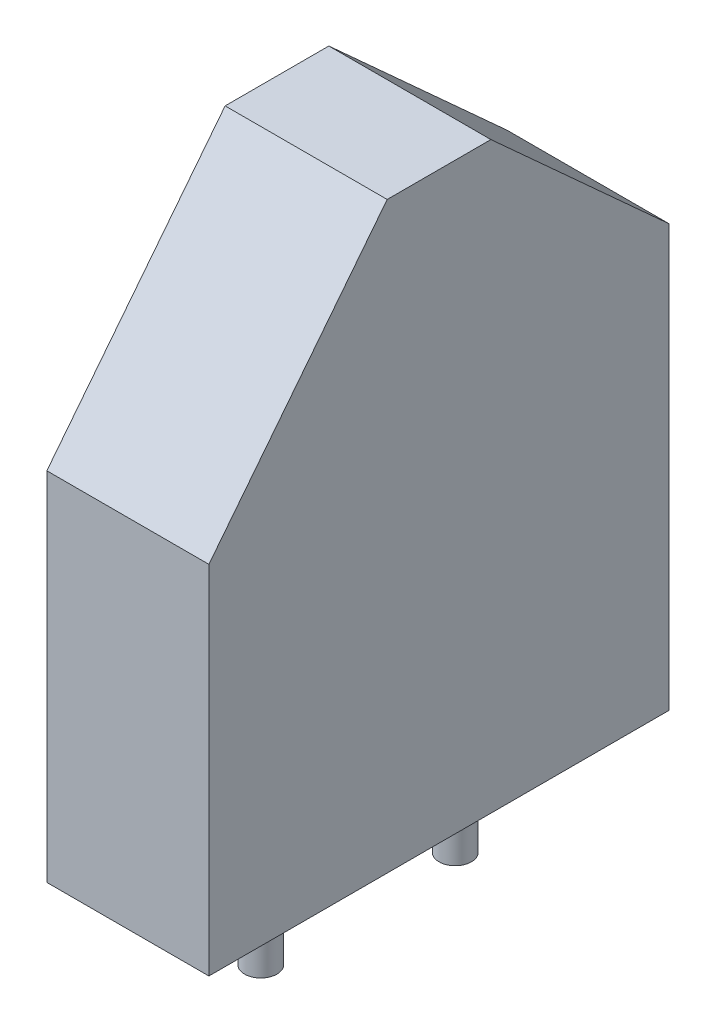
SolidWorks part; units mm, degrees
ref_plane "前视基准面" through (0, 0, 0) normal (0, 0, 1) x (1, 0, 0)
ref_plane "上视基准面" through (0, 0, 0) normal (0, 1, 0) x (1, 0, 0)
ref_plane "右视基准面" through (0, 0, 0) normal (1, 0, 0) x (0, 0, -1)
sketch "草图1" plane through (0, 0, 0) normal (0, 1, 0) x (1, 0, 0)
  line L0 (-45.7415, 0) -> (52.4503, 0) construction
  line L1 (-2.5, 7.1) -> (2.5, 7.1)
  line L2 (-2.5, 7.1) -> (-2.5, -7.1)
  line L3 (-2.5, -7.1) -> (2.5, -7.1)
  line L4 (2.5, 7.1) -> (2.5, -7.1)
  line L5 (0, 37.5081) -> (0, -35.6784) construction
  dimension "D1" = 5
  dimension "D2" = 14.2
extrude "拉伸1" add sketch "草图1" along normal blind 18
sketch "草图2" plane through (0, 0, 0) normal (0, -1, 0) x (1, 0, 0)
  line L0 (0, -7.7319) -> (0, 7.3875) construction
  line L1 (3.4268, 0) -> (-3.9951, 0) construction
  circle A0 centre (0, 3) radius 0.5
  circle A1 centre (0, -3) radius 0.5
  dimension "D2" = 1
  dimension "D3" = 1
  dimension "D1" = 3
  dimension "D4" = 3
extrude "拉伸2" add sketch "草图2" along normal blind 3
sketch "草图3" plane through (2.5, 0, 0) normal (1, 0, 0) x (0, 0, -1)
  line L0 (0, -1.7938) -> (0, 18.4087) construction
  line L1 (-1.6, 18) -> (-7.1, 11)
  line L2 (-7.1, 18) -> (7.1, 18) construction
  line L3 (-7.1, 18) -> (-7.1, 0) construction
  line L4 (1.6, 18) -> (7.1, 13)
  line L5 (7.1, 18) -> (7.1, 0) construction
  line L6 (-7.1, 11) -> (-7.1, 18)
  line L7 (-7.1, 18) -> (-1.6, 18)
  line L8 (7.1, 13) -> (7.1, 18)
  line L9 (7.1, 18) -> (1.6, 18)
  dimension "D1" = 1.6
  dimension "D2" = 7
  dimension "D3" = 1.6
  dimension "D4" = 5
extrude "切除-拉伸1" cut sketch "草图3" against normal blind 5
